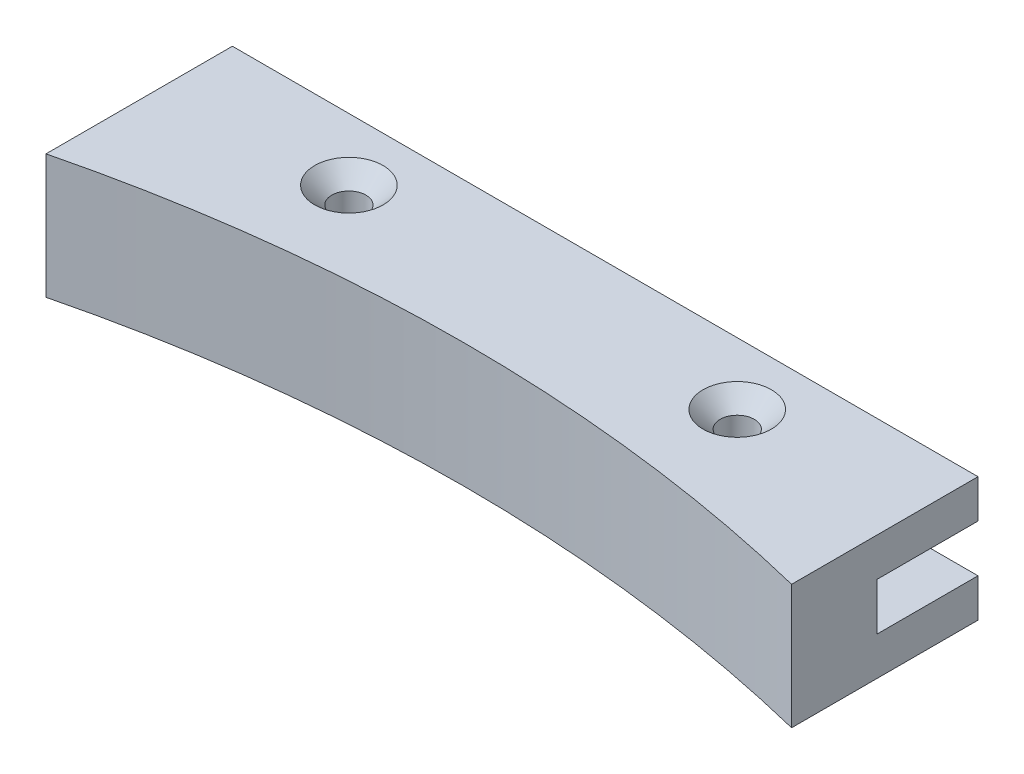
SolidWorks part; units mm, degrees
material "6061-T6 (SS)"
ref_plane "Front Plane" through (0, 0, 0) normal (0, 0, 1) x (1, 0, 0)
ref_plane "Top Plane" through (0, 0, 0) normal (0, 1, 0) x (1, 0, 0)
ref_plane "Right Plane" through (0, 0, 0) normal (1, 0, 0) x (0, 0, -1)
sketch "Sketch1" plane through (0, 0, 0) normal (0, 1, 0) x (1, 0, 0)
  line L0 (-24, 0) -> (24, 0)
  line L1 (24, 0) -> (24, -12)
  line L2 (-24, 0) -> (-24, -12)
  line L3 (-24, -9.0773) -> (24, -9.0773) construction
  line L25 (-24, -12) -> (0, -109.0773) construction
  line L26 (0, -109.0773) -> (24, -12) construction
  arc A0 (-24, -12) -> (24, -12) centre (0, -109.0773) cw
  point P0 (0, 0)
  dimension "D1" = 12
  dimension "D2" = 100
  dimension "D5" = 48
extrude "Boss-Extrude1" add sketch "Sketch1" along normal mid plane 8
hole_wizard "CSK for M2 Flat Head Machine Screw1" positions "Sketch10" profile "Sketch11" countersink size "M2" standard "ANSI Metric" end condition through all
sketch "Sketch10" plane through (0, 4, 0) normal (0, 1, 0) x (1, 0, 0)
  line L0 (0, -0.121) -> (0, -16.3024) construction
  line L1 (24, 0) -> (-24, 0) construction
  point P8 (-12.5, -4)
  point P13 (12.5, -4)
  dimension "D1" = 12.5
  dimension "D2" = 4
sketch "Sketch11" plane through (12.5, 4, 4) normal (1, 0, 0) x (0, 0, 1)
  line L0 (0, 0) -> (0, 8)
  line L1 (0, 8) -> (1.1, 8)
  line L2 (1.1, 8) -> (1.1, 1.1)
  line L3 (1.1, 1.1) -> (2.2, 0)
  line L5 (2.2, 0) -> (0, 0)
  line L6 (-1.1, 1.1) -> (-2.2, 0) construction
  line L11 (0, -6.35) -> (0, 107.95) construction
  dimension "Thru Hole Dia." = 2.2
  dimension "Thru Hole Depth" = 8
  dimension "Near C'Sink Dia." = 4.4
  dimension "Near C'Sink Angle" = 90
sketch "Sketch9" plane through (-24, 0, 0) normal (-1, 0, 0) x (0, 0, 1)
  line L0 (0, 4) -> (0, -4) construction
  line L1 (0, -1.525) -> (6.5, -1.525)
  line L2 (0, -1.525) -> (0, 1.525)
  line L3 (0, 1.525) -> (6.5, 1.525)
  line L4 (6.5, -1.525) -> (6.5, 1.525)
  point P6 (0, 0)
  dimension "D1" = 3.05
  dimension "D2" = 6.5
extrude "Cut-Extrude2" cut sketch "Sketch9" against normal through all
